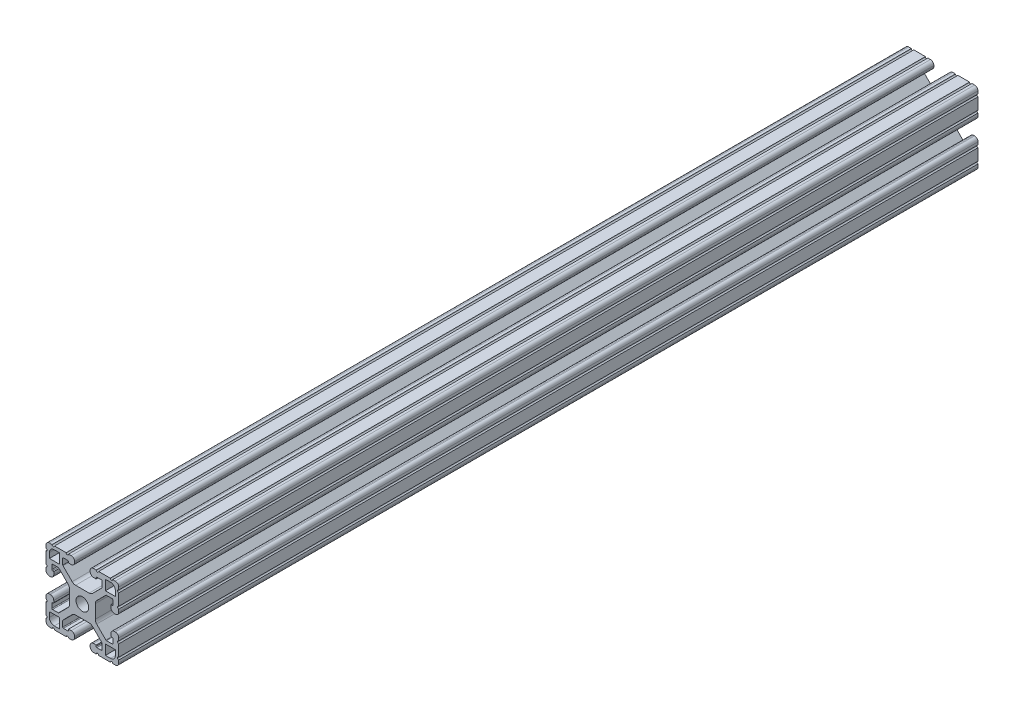
SolidWorks part; units mm, degrees
ref_plane "Front Plane" through (0, 0, 0) normal (0, 0, 1) x (1, 0, 0)
ref_plane "Top Plane" through (0, 0, 0) normal (0, 1, 0) x (1, 0, 0)
ref_plane "Right Plane" through (0, 0, 0) normal (1, 0, 0) x (0, 0, -1)
sketch "Sketch1" plane through (0, 0, 0) normal (0, 0, 1) x (1, 0, 0)
  line L0 (0, -19.05) -> (0, 19.05) construction
  line L1 (19.05, 0) -> (-19.05, 0) construction
  line L2 (4.064, 19.05) -> (-4.064, 19.05) construction
  line L3 (0, -6.7564) -> (0, 6.7564) construction
  line L4 (-4.064, 19.05) -> (-4.064, 14.986) construction
  line L5 (19.05, -10.287) -> (19.05, 10.287) construction
  line L6 (0, -3.3274) -> (0, 3.3274) construction
  line L7 (0, 0) -> (-19.05, 19.05) construction
  line L8 (-8.4474, 10.6026) -> (-10.6026, 8.4474) construction
  point P4 (0, 0)
  point P8 (0, 0)
  point P11 (0, 19.05)
  point P14 (0, 0)
  point P18 (19.05, 0)
  point P21 (0, 0)
  point P24 (-9.525, 9.525)
  point P26 (-9.525, 9.525)
  dimension "T-Slot Width" = 8.128
  dimension "Thickness" = 4.064
  dimension "Opening Width" = 20.574
  dimension "Slot Depth" = 12.2936
  dimension "Center Hole Diameter" = 6.6548
  dimension "Rail Height" = 38.1
  dimension "Rail Width" = 38.1
  dimension "D1" = 45
  dimension "Wall" = 3.048
sketch "Sketch2" plane through (0, 0, 0) normal (1, 0, 0) x (0, 0, -1)
  line L0 (-457.2, 0) -> (457.2, 0) construction
  line L1 (-381, -19.05) -> (-381, 19.05) construction
  line L2 (381, -19.05) -> (381, 19.05) construction
  line L3 (0, -19.05) -> (0, 19.05) construction
  point P4 (0, 0)
  point P7 (-381, 0)
  point P10 (381, 0)
  dimension "Length" = 914.4
  dimension "D1" = 76.2
  dimension "D2" = 76.2
sketch "Sketch3" plane through (0, 0, 0) normal (0, 0, 1) x (1, 0, 0)
  line L1 (19.05, -19.05) -> (-19.05, -19.05)
  line L2 (19.05, -19.05) -> (19.05, 19.05)
  line L3 (19.05, 19.05) -> (-19.05, 19.05)
  line L4 (-19.05, -19.05) -> (-19.05, 19.05)
  line L5 (19.05, -19.05) -> (-19.05, 19.05) construction
  line L6 (19.05, 19.05) -> (-19.05, -19.05) construction
  point P0 (0, 0)
extrude "Boss-Extrude1" add sketch "Sketch3" along normal blind 43.815 and the other way blind 406.4
sketch "Sketch4" plane through (0, 0, 43.815) normal (0, 0, 1) x (1, 0, 0)
  line L4 (4.064, 14.986) -> (4.064, 19.05)
  line L5 (7.239, 14.986) -> (4.064, 14.986)
  line L6 (19.05, 0) -> (-19.05, 0) construction
  line L7 (4.6011, 6.7564) -> (-4.6011, 6.7564)
  line L8 (-4.6011, 6.7564) -> (-10.287, 12.4423)
  line L37 (-19.05, 19.05) -> (-19.05, -19.05) construction
  line L38 (-19.05, -19.05) -> (19.05, -19.05) construction
  line L39 (-10.287, 12.4423) -> (-10.287, 16.002)
  line L40 (-10.287, 16.002) -> (-7.239, 16.002)
  line L41 (-7.239, 16.002) -> (-7.239, 14.986)
  line L42 (-7.239, 14.986) -> (-4.064, 14.986)
  line L43 (-4.064, 14.986) -> (-4.064, 19.05)
  line L44 (-4.064, 19.05) -> (4.064, 19.05)
  line L45 (0, 19.05) -> (0, 0) construction
  line L46 (-19.05, 19.05) -> (0, 0) construction
  line L47 (7.239, 16.002) -> (7.239, 14.986)
  line L48 (10.287, 16.002) -> (7.239, 16.002)
  line L49 (10.287, 12.4423) -> (10.287, 16.002)
  line L50 (4.6011, 6.7564) -> (10.287, 12.4423)
  line L51 (-19.05, 0) -> (19.05, 0) construction
  line L52 (4.6011, -6.7564) -> (10.287, -12.4423)
  line L53 (10.287, -12.4423) -> (10.287, -16.002)
  line L54 (10.287, -16.002) -> (7.239, -16.002)
  line L55 (7.239, -16.002) -> (7.239, -14.986)
  line L56 (-4.064, -19.05) -> (4.064, -19.05)
  line L57 (-4.064, -14.986) -> (-4.064, -19.05)
  line L58 (-7.239, -14.986) -> (-4.064, -14.986)
  line L59 (-7.239, -16.002) -> (-7.239, -14.986)
  line L60 (-10.287, -16.002) -> (-7.239, -16.002)
  line L61 (-10.287, -12.4423) -> (-10.287, -16.002)
  line L62 (-4.6011, -6.7564) -> (-10.287, -12.4423)
  line L63 (4.6011, -6.7564) -> (-4.6011, -6.7564)
  line L64 (7.239, -14.986) -> (4.064, -14.986)
  line L65 (4.064, -14.986) -> (4.064, -19.05)
  line L66 (-6.7564, -4.6011) -> (-12.4423, -10.287)
  line L67 (-12.4423, -10.287) -> (-16.002, -10.287)
  line L68 (-16.002, -10.287) -> (-16.002, -7.239)
  line L69 (-16.002, -7.239) -> (-14.986, -7.239)
  line L70 (-19.05, 4.064) -> (-19.05, -4.064)
  line L71 (-14.986, 4.064) -> (-19.05, 4.064)
  line L72 (-14.986, 7.239) -> (-14.986, 4.064)
  line L73 (-16.002, 7.239) -> (-14.986, 7.239)
  line L74 (-16.002, 10.287) -> (-16.002, 7.239)
  line L75 (-12.4423, 10.287) -> (-16.002, 10.287)
  line L76 (-6.7564, 4.6011) -> (-12.4423, 10.287)
  line L77 (-6.7564, -4.6011) -> (-6.7564, 4.6011)
  line L78 (-14.986, -7.239) -> (-14.986, -4.064)
  line L79 (-14.986, -4.064) -> (-19.05, -4.064)
  line L80 (14.986, -4.064) -> (19.05, -4.064)
  line L81 (14.986, -7.239) -> (14.986, -4.064)
  line L82 (6.7564, -4.6011) -> (6.7564, 4.6011)
  line L83 (6.7564, 4.6011) -> (12.4423, 10.287)
  line L84 (12.4423, 10.287) -> (16.002, 10.287)
  line L85 (16.002, 10.287) -> (16.002, 7.239)
  line L86 (16.002, 7.239) -> (14.986, 7.239)
  line L87 (14.986, 7.239) -> (14.986, 4.064)
  line L88 (14.986, 4.064) -> (19.05, 4.064)
  line L89 (19.05, 4.064) -> (19.05, -4.064)
  line L90 (16.002, -7.239) -> (14.986, -7.239)
  line L91 (16.002, -10.287) -> (16.002, -7.239)
  line L92 (12.4423, -10.287) -> (16.002, -10.287)
  line L93 (6.7564, -4.6011) -> (12.4423, -10.287)
  line L94 (19.05, -19.05) -> (19.05, 19.05) construction
  line L95 (12.065, 17.272) -> (17.272, 17.272)
  line L96 (12.065, 17.272) -> (12.065, 12.065)
  line L97 (12.065, 12.065) -> (17.272, 12.065)
  line L98 (17.272, 17.272) -> (17.272, 12.065)
  line L99 (19.05, 19.05) -> (-19.05, 19.05) construction
  line L100 (17.272, -17.272) -> (17.272, -12.065)
  line L101 (12.065, -17.272) -> (17.272, -17.272)
  line L102 (12.065, -17.272) -> (12.065, -12.065)
  line L103 (12.065, -12.065) -> (17.272, -12.065)
  line L104 (-17.272, 17.272) -> (-17.272, 12.065)
  line L105 (-12.065, 12.065) -> (-17.272, 12.065)
  line L106 (-12.065, 17.272) -> (-12.065, 12.065)
  line L107 (-12.065, 17.272) -> (-17.272, 17.272)
  line L108 (-12.065, -12.065) -> (-17.272, -12.065)
  line L109 (-12.065, -17.272) -> (-12.065, -12.065)
  line L110 (-12.065, -17.272) -> (-17.272, -17.272)
  line L111 (-17.272, -17.272) -> (-17.272, -12.065)
  circle A5 centre (0, 0) radius 3.3274
  point P21 (0, 6.7564)
  point P23 (0, -6.7564)
  point P38 (-6.7564, 0)
  point P53 (6.7564, 0)
  dimension "D1" = 20.574
  dimension "D3" = 3.048
  dimension "D4" = 3.048
  dimension "D5" = 1.778
  dimension "D6" = 1.778
  dimension "D7" = 1.778
extrude "Cut-Extrude1" cut sketch "Sketch4" against normal through all
sketch "Sketch5" plane through (0, 0, 43.815) normal (0, 0, 1) x (1, 0, 0)
  line L4 (-4.064, 19.05) -> (-19.05, 19.05) construction
  line L26 (-19.05, 19.05) -> (-19.05, 4.064) construction
  line L27 (-15.875, 19.05) -> (-14.605, 19.05)
  line L28 (-8.509, 19.05) -> (-7.239, 19.05)
  line L29 (-19.05, 15.875) -> (-19.05, 14.605)
  line L30 (-19.05, 8.509) -> (-19.05, 7.239)
  line L31 (8.509, 19.05) -> (7.239, 19.05)
  line L32 (15.875, 19.05) -> (14.605, 19.05)
  line L33 (19.05, 15.875) -> (19.05, 14.605)
  line L34 (19.05, 8.509) -> (19.05, 7.239)
  line L35 (19.05, -8.509) -> (19.05, -7.239)
  line L36 (19.05, -15.875) -> (19.05, -14.605)
  line L37 (15.875, -19.05) -> (14.605, -19.05)
  line L38 (8.509, -19.05) -> (7.239, -19.05)
  line L39 (-8.509, -19.05) -> (-7.239, -19.05)
  line L40 (-15.875, -19.05) -> (-14.605, -19.05)
  line L41 (-19.05, -15.875) -> (-19.05, -14.605)
  line L42 (-19.05, -8.509) -> (-19.05, -7.239)
  line L43 (19.05, 19.05) -> (4.064, 19.05) construction
  line L44 (19.05, 4.064) -> (19.05, 19.05) construction
  line L48 (-14.986, 4.064) -> (-19.05, 4.064) construction
  line L49 (-4.064, 14.986) -> (-4.064, 19.05) construction
  arc A8 (-15.875, 19.05) -> (-14.605, 19.05) centre (-15.24, 19.05) ccw
  arc A9 (-8.509, 19.05) -> (-7.239, 19.05) centre (-7.874, 19.05) ccw
  arc A10 (-19.05, 14.605) -> (-19.05, 15.875) centre (-19.05, 15.24) ccw
  arc A11 (-19.05, 7.239) -> (-19.05, 8.509) centre (-19.05, 7.874) ccw
  arc A12 (7.239, 19.05) -> (8.509, 19.05) centre (7.874, 19.05) ccw
  arc A13 (14.605, 19.05) -> (15.875, 19.05) centre (15.24, 19.05) ccw
  arc A14 (19.05, 15.875) -> (19.05, 14.605) centre (19.05, 15.24) ccw
  arc A15 (19.05, 8.509) -> (19.05, 7.239) centre (19.05, 7.874) ccw
  arc A16 (19.05, -7.239) -> (19.05, -8.509) centre (19.05, -7.874) ccw
  arc A17 (19.05, -14.605) -> (19.05, -15.875) centre (19.05, -15.24) ccw
  arc A18 (15.875, -19.05) -> (14.605, -19.05) centre (15.24, -19.05) ccw
  arc A19 (8.509, -19.05) -> (7.239, -19.05) centre (7.874, -19.05) ccw
  arc A20 (-7.239, -19.05) -> (-8.509, -19.05) centre (-7.874, -19.05) ccw
  arc A21 (-14.605, -19.05) -> (-15.875, -19.05) centre (-15.24, -19.05) ccw
  arc A22 (-19.05, -15.875) -> (-19.05, -14.605) centre (-19.05, -15.24) ccw
  arc A23 (-19.05, -8.509) -> (-19.05, -7.239) centre (-19.05, -7.874) ccw
  dimension "D2" = 0.635
  dimension "D4" = 3.81
  dimension "D5" = 3.81
  dimension "D1" = 3.81
  dimension "D3" = 3.81
  dimension "D7" = 4
extrude "Cut-Extrude2" cut sketch "Sketch5" against normal through all
fillet "Fillet1" radius 2.54 12 edges at (-6.7564, 4.6011, -181.2925) (-6.7564, -4.6011, -181.2925) (4.6011, -6.7564, -181.2925) (-4.6011, -6.7564, -181.2925) (6.7564, -4.6011, -181.2925) (6.7564, 4.6011, -181.2925) (4.6011, 6.7564, -181.2925) (-4.6011, 6.7564, -181.2925) (-17.272, 17.272, -181.2925) (17.272, 17.272, -181.2925) (17.272, -17.272, -181.2925) (-17.272, -17.272, -181.2925)
fillet "Fillet2" radius 1.778 20 edges at (19.05, -19.05, -181.2925) (19.05, 19.05, -181.2925) (-19.05, -19.05, -181.2925) (-19.05, 19.05, -181.2925) (-14.986, 4.064, -181.2925) (-19.05, 4.064, -181.2925) (-19.05, -4.064, -181.2925) (-14.986, -4.064, -181.2925) (-4.064, -19.05, -181.2925) (-4.064, -14.986, -181.2925) (4.064, -14.986, -181.2925) (4.064, -19.05, -181.2925) (19.05, -4.064, -181.2925) (14.986, -4.064, -181.2925) (19.05, 4.064, -181.2925) (14.986, 4.064, -181.2925) (4.064, 14.986, -181.2925) (4.064, 19.05, -181.2925) (-4.064, 19.05, -181.2925) (-4.064, 14.986, -181.2925)
fillet "Fillet3" radius 0.3969 24 edges at (-14.986, -7.239, -181.2925) (-16.002, -10.287, -181.2925) (-12.4423, -10.287, -181.2925) (-12.4423, 10.287, -181.2925) (-16.002, 7.239, -181.2925) (-16.002, 10.287, -181.2925) (-10.287, 12.4423, -181.2925) (-7.239, 16.002, -181.2925) (-10.287, 16.002, -181.2925) (10.287, 16.002, -181.2925) (7.239, 16.002, -181.2925) (10.287, 12.4423, -181.2925) (16.002, 10.287, -181.2925) (12.4423, 10.287, -181.2925) (16.002, 7.239, -181.2925) (16.002, -7.239, -181.2925) (16.002, -10.287, -181.2925) (12.4423, -10.287, -181.2925) (10.287, -12.4423, -181.2925) (10.287, -16.002, -181.2925) (7.239, -16.002, -181.2925) (-7.239, -16.002, -181.2925) (-10.287, -12.4423, -181.2925) (-10.287, -16.002, -181.2925)
equation "\"D4@Sketch5\"=\"D3@Sketch5\""
equation "\"D5@Sketch5\"=\"D4@Sketch5\""
equation "\"D1@Sketch4\"=\"Opening Width@Sketch1\""
equation "\"D2@Sketch2\"=\"D1@Sketch2\""
